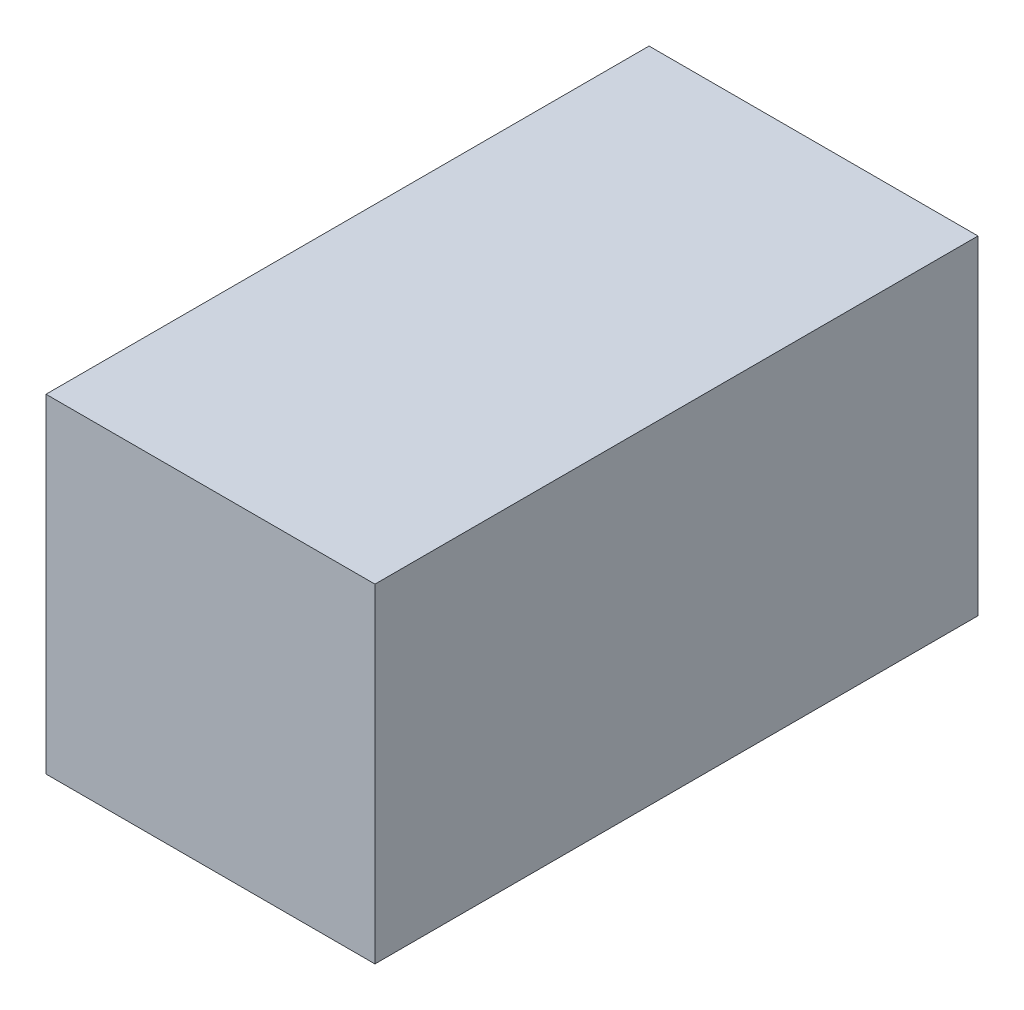
SolidWorks part; units mm, degrees
ref_plane "Front Plane" through (0, 0, 0) normal (0, 0, 1) x (1, 0, 0)
ref_plane "Top Plane" through (0, 0, 0) normal (0, 1, 0) x (1, 0, 0)
ref_plane "Right Plane" through (0, 0, 0) normal (1, 0, 0) x (0, 0, -1)
sketch "Sketch1" plane through (0, 0, 0) normal (0, 0, 1) x (1, 0, 0)
  line L1 (0, 0) -> (76.2, 0)
  line L2 (0, 0) -> (0, 76.2)
  line L3 (0, 76.2) -> (76.2, 76.2)
  line L4 (76.2, 0) -> (76.2, 76.2)
  dimension "D1" = 76.2
extrude "Boss-Extrude1" add sketch "Sketch1" along normal blind 139.7
